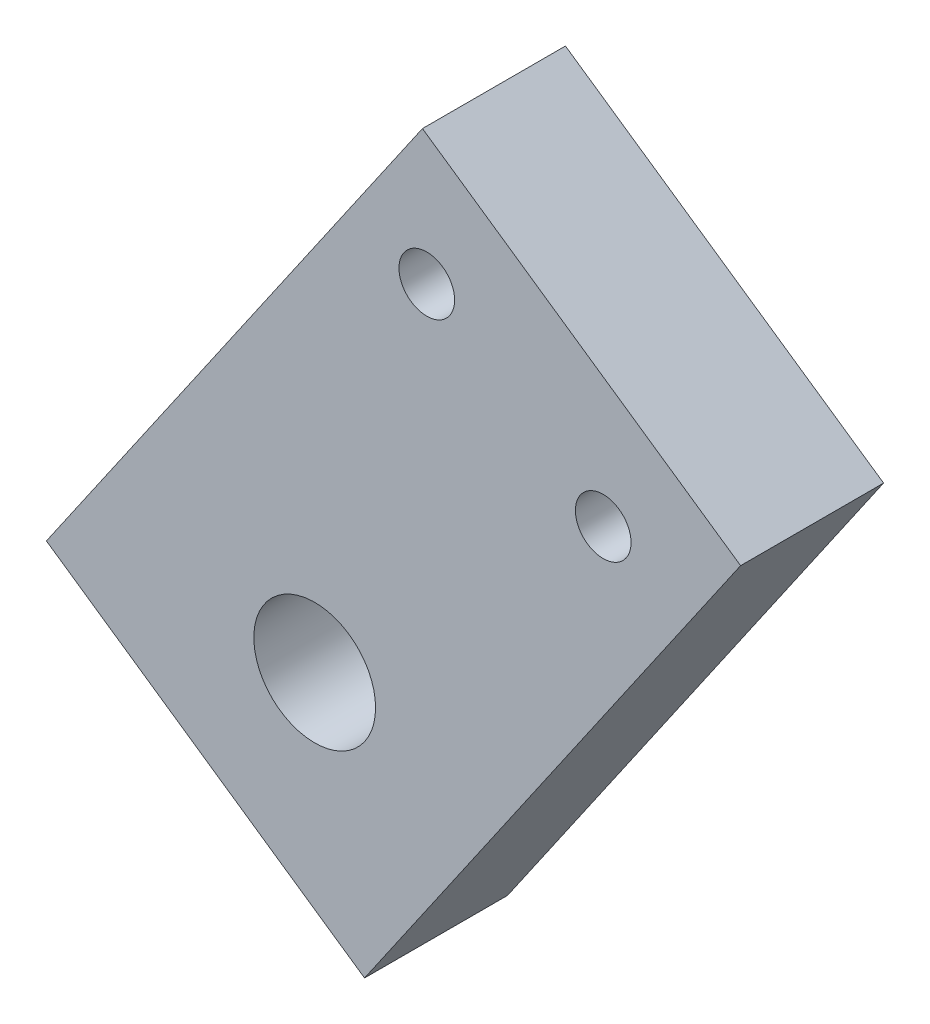
SolidWorks part; units mm, degrees
ref_plane "Front Plane" through (0, 0, 0) normal (0, 0, 1) x (1, 0, 0)
ref_plane "Top Plane" through (0, 0, 0) normal (0, 1, 0) x (1, 0, 0)
ref_plane "Right Plane" through (0, 0, 0) normal (1, 0, 0) x (0, 0, -1)
sketch "Sketch1" plane through (0, 0, 0) normal (0, 0, 1) x (1, 0, 0)
  line L0 (-74.5781, -79.1004) -> (-62.9827, -87.0993) construction
  line L1 (-99.5767, -106.2179) -> (-74.8622, -70.3912)
  line L2 (-78.6688, -120.6409) -> (-53.9544, -84.8141)
  line L3 (-74.8622, -70.3912) -> (-53.9544, -84.8141)
  line L6 (-99.5767, -106.2179) -> (-78.6688, -120.6409)
  circle A0 centre (-81.945, -104.8964) radius 4.0005
  circle A1 centre (-74.5781, -79.1004) radius 1.8288
  circle A2 centre (-62.9827, -87.0993) radius 1.8288
  dimension "D1" = 25.4
extrude "Boss-Extrude1" add sketch "Sketch1" along normal blind 9.398
